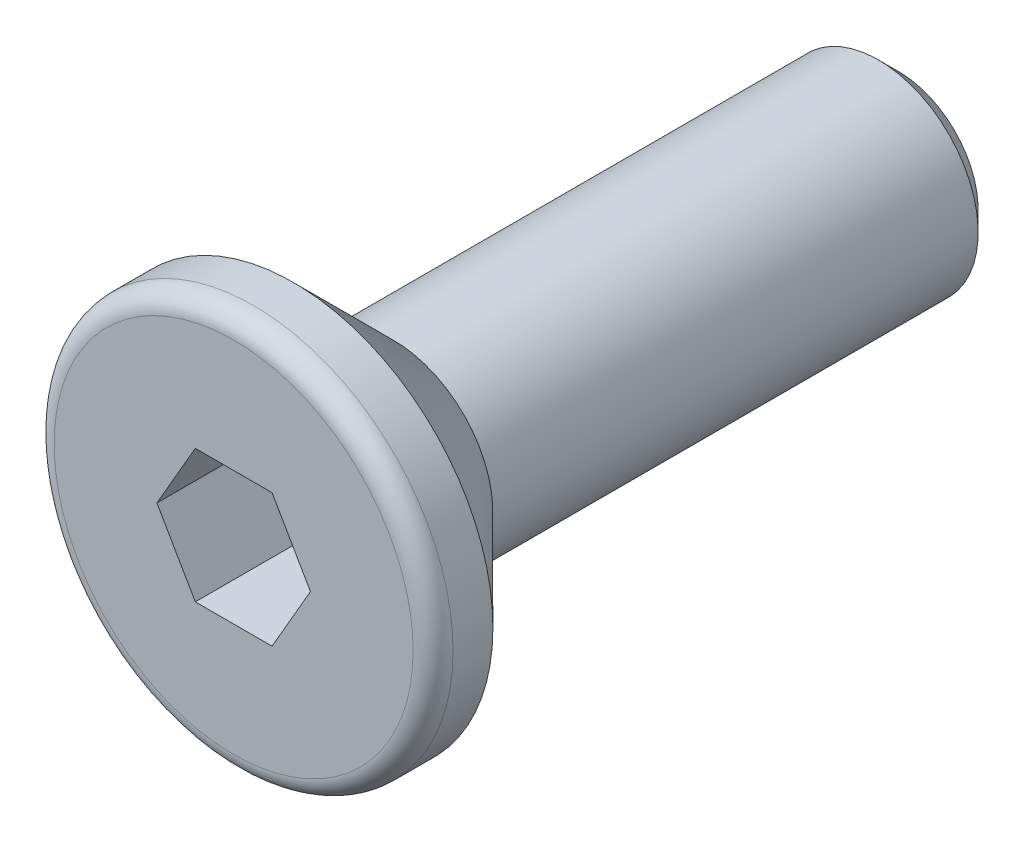
SolidWorks part; units mm, degrees
ref_plane "前视基准面" through (0, 0, 0) normal (0, 0, 1) x (1, 0, 0)
ref_plane "上视基准面" through (0, 0, 0) normal (0, 1, 0) x (1, 0, 0)
ref_plane "右视基准面" through (0, 0, 0) normal (1, 0, 0) x (0, 0, -1)
sketch "草图1" plane through (0, 0, 0) normal (1, 0, 0) x (0, 0, -1)
  line L0 (-5, 0) -> (-5, 3)
  line L1 (-5, 3) -> (-4.1, 3)
  line L2 (-4.1, 3) -> (-2.6, 1.5)
  line L3 (-2.6, 1.5) -> (4.7, 1.5)
  line L4 (4.7, 1.5) -> (5, 1.2)
  line L5 (5, 1.2) -> (5, 0)
  line L6 (5, 0) -> (-5, 0)
  dimension "D1" = 10
  dimension "D2" = 3
  dimension "D3" = 45
  dimension "D4" = 0.3
  dimension "D5" = 2.4
  dimension "D6" = 1.5
revolve "旋转1" add sketch "草图1" angle 360 about L6
sketch "草图2" plane through (0, 0, 5) normal (0, 0, 1) x (1, 0, 0)
  line L1 (1.1547, 0) -> (0.5774, 1)
  line L2 (0.5774, 1) -> (-0.5774, 1)
  line L3 (-0.5774, 1) -> (-1.1547, 0)
  line L4 (-1.1547, 0) -> (-0.5774, -1)
  line L5 (-0.5774, -1) -> (0.5774, -1)
  line L6 (0.5774, -1) -> (1.1547, 0)
  circle A0 centre (0, 0) radius 1 construction
  dimension "D1" = 2
extrude "切除-拉伸1" cut sketch "草图2" against normal blind 1.5
fillet "圆角1" radius 0.3 1 edges at (-3, 0, 5)
